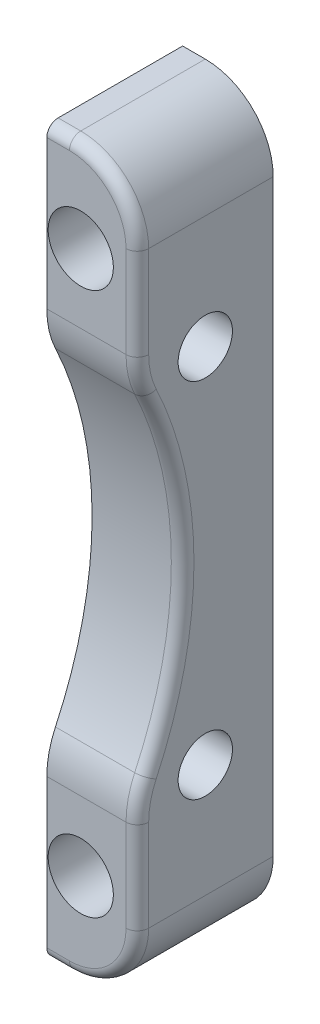
SolidWorks part; units mm, degrees
ref_plane "Front Plane" through (0, 0, 0) normal (0, 0, 1) x (1, 0, 0)
ref_plane "Top Plane" through (0, 0, 0) normal (0, 1, 0) x (1, 0, 0)
ref_plane "Right Plane" through (0, 0, 0) normal (1, 0, 0) x (0, 0, -1)
sketch "Sketch1" plane through (0, 0, 0) normal (1, 0, 0) x (0, 0, -1)
  line L0 (0, -25.4) -> (0, 25.4)
  line L1 (0, 25.4) -> (-9.525, 25.4)
  line L2 (-9.525, 25.4) -> (-9.525, 12.7)
  line L3 (0, -25.4) -> (-9.525, -25.4)
  line L4 (-9.525, -25.4) -> (-9.525, -12.7)
  arc A0 (-9.525, 12.7) -> (-9.525, -12.7) centre (-33.3375, 0) cw
  point P8 (0, 0)
  point P9 (-14.199, -12.7)
  point P10 (-6.35, 0)
  dimension "D1" = 9.525
  dimension "D2" = 50.8
  dimension "D3" = 12.7
  dimension "D4" = 6.35
extrude "Boss-Extrude1" add sketch "Sketch1" along normal blind 6.35
sketch "Sketch2" plane through (0, 0, 9.525) normal (0, 0, 1) x (1, 0, 0)
  line L0 (2.3813, 19.05) -> (2.3813, -19.05) construction
  circle A0 centre (2.3813, 19.05) radius 2.286
  circle A1 centre (2.3813, -19.05) radius 2.286
  arc A2 (2.3813, 17.3228) -> (2.3813, 20.7772) centre (2.3813, 19.05) ccw construction
  point P4 (2.3813, 0)
  point P5 (2.6351, 19.0265)
  dimension "D1" = 4.572
extrude "Cut-Extrude1" cut sketch "Sketch2" against normal up to next
sketch "Sketch3" plane through (6.35, 0, 0) normal (1, 0, 0) x (0, 0, -1)
  circle A0 centre (-4.7625, 12.7) radius 1.905
  circle A1 centre (-4.7625, -12.7) radius 1.905
  circle A2 centre (-4.7625, 12.7) radius 2.032 construction
  circle A3 centre (-4.7625, -12.7) radius 2.032 construction
  dimension "D1" = 3.81
extrude "Cut-Extrude2" cut sketch "Sketch3" against normal up to next
fillet "Fillet1" radius 4.7625 2 edges at (6.35, -25.4, 4.7625) (6.35, 25.4, 4.7625)
fillet "Fillet2" radius 6.35 2 edges at (3.175, -12.7, 9.525) (3.175, 12.7, 9.525)
fillet "Fillet3" radius 0.7937 9 edges at (0.7937, 25.4, 9.525) (4.9551, 24.0051, 9.525) (0.7937, -25.4, 9.525) (4.9551, -24.0051, 9.525) (6.35, -17.4183, 9.525) (6.35, -12.8133, 9.372) (6.35, 0, 6.35) (6.35, 12.8133, 9.372) (6.35, 17.4183, 9.525)
